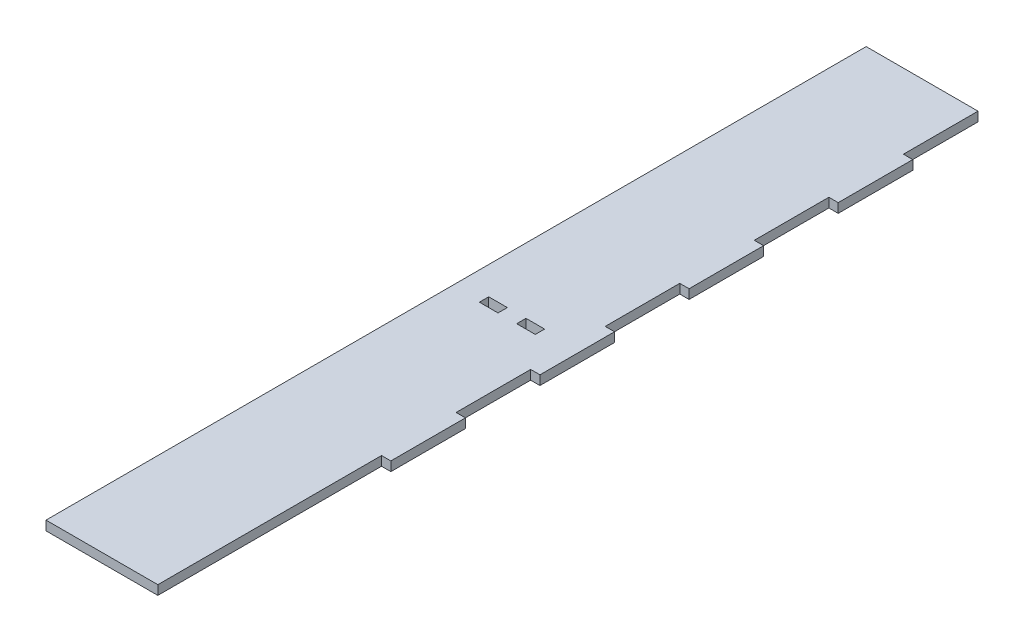
SolidWorks part; units mm, degrees
ref_plane "Front Plane" through (0, 0, 0) normal (0, 0, 1) x (1, 0, 0)
ref_plane "Top Plane" through (0, 0, 0) normal (0, 1, 0) x (1, 0, 0)
ref_plane "Right Plane" through (0, 0, 0) normal (1, 0, 0) x (0, 0, -1)
sketch "Sketch1" plane through (0, 0, 0) normal (0, 0, 1) x (1, 0, 0)
  line L1 (38.1, 38.1) -> (-38.1, 38.1)
  line L2 (38.1, 38.1) -> (38.1, 44.45)
  line L3 (38.1, 44.45) -> (-38.1, 44.45)
  line L4 (-38.1, 38.1) -> (-38.1, 44.45)
extrude "Boss-Extrude1" add sketch "Sketch1" along normal blind 558.8
sketch "Sketch2" plane through (0, 44.45, 0) normal (0, 1, 0) x (1, 0, 0)
  line L0 (0, -558.8) -> (0, 0) construction
  line L1 (38.1, -558.8) -> (-38.1, -558.8) construction
  line L2 (0, -279.4) -> (-28.148, -279.4) construction
  line L4 (19.05, -282.575) -> (6.35, -282.575)
  line L5 (19.05, -282.575) -> (19.05, -276.225)
  line L6 (19.05, -276.225) -> (6.35, -276.225)
  line L7 (6.35, -282.575) -> (6.35, -276.225)
  line L8 (-6.35, -282.575) -> (-19.05, -282.575)
  line L9 (-6.35, -282.575) -> (-6.35, -276.225)
  line L10 (-6.35, -276.225) -> (-19.05, -276.225)
  line L11 (-19.05, -282.575) -> (-19.05, -276.225)
  dimension "D1" = 6.35
  dimension "D2" = 6.35
  dimension "D3" = 12.7
  dimension "D4" = 12.7
  dimension "D5" = 12.7
extrude "Cut-Extrude1" cut sketch "Sketch2" against normal through all
sketch "Sketch3" plane through (38.1, 0, 0) normal (1, 0, 0) x (0, 0, -1)
  line L0 (-558.8, 38.1) -> (0, 38.1) construction
  line L1 (-406.4, 38.1) -> (-355.6, 38.1)
  line L2 (-406.4, 38.1) -> (-406.4, 44.45)
  line L3 (-406.4, 44.45) -> (-355.6, 44.45)
  line L4 (-355.6, 38.1) -> (-355.6, 44.45)
  line L5 (-558.8, 44.45) -> (0, 44.45) construction
  line L6 (-355.6, 38.1) -> (-355.6, 44.45) construction
  line L7 (-406.4, 44.45) -> (-406.4, 38.1) construction
  line L8 (-304.8, 44.45) -> (-304.8, 38.1) construction
  line L9 (-304.8, 44.45) -> (-254, 44.45)
  line L10 (-304.8, 44.45) -> (-304.8, 38.1)
  line L11 (-304.8, 38.1) -> (-254, 38.1)
  line L12 (-254, 44.45) -> (-254, 38.1)
  line L13 (-203.2, 44.45) -> (-203.2, 38.1) construction
  line L14 (-203.2, 44.45) -> (-152.4, 44.45)
  line L15 (-203.2, 44.45) -> (-203.2, 38.1)
  line L16 (-203.2, 38.1) -> (-152.4, 38.1)
  line L17 (-152.4, 44.45) -> (-152.4, 38.1)
  line L18 (-101.6, 44.45) -> (-101.6, 38.1) construction
  line L19 (-101.6, 44.45) -> (-50.8, 44.45)
  line L20 (-101.6, 44.45) -> (-101.6, 38.1)
  line L21 (-101.6, 38.1) -> (-50.8, 38.1)
  line L22 (-50.8, 44.45) -> (-50.8, 38.1)
  line L23 (-254, 38.1) -> (-254, 44.45) construction
  line L24 (-152.4, 38.1) -> (-152.4, 44.45) construction
  line L25 (-101.6, 38.1) -> (-50.8, 38.1) construction
  line L26 (-50.8, 38.1) -> (-50.8, 44.45) construction
extrude "Boss-Extrude2" add sketch "Sketch3" along normal up to surface (6.35 mm away)
